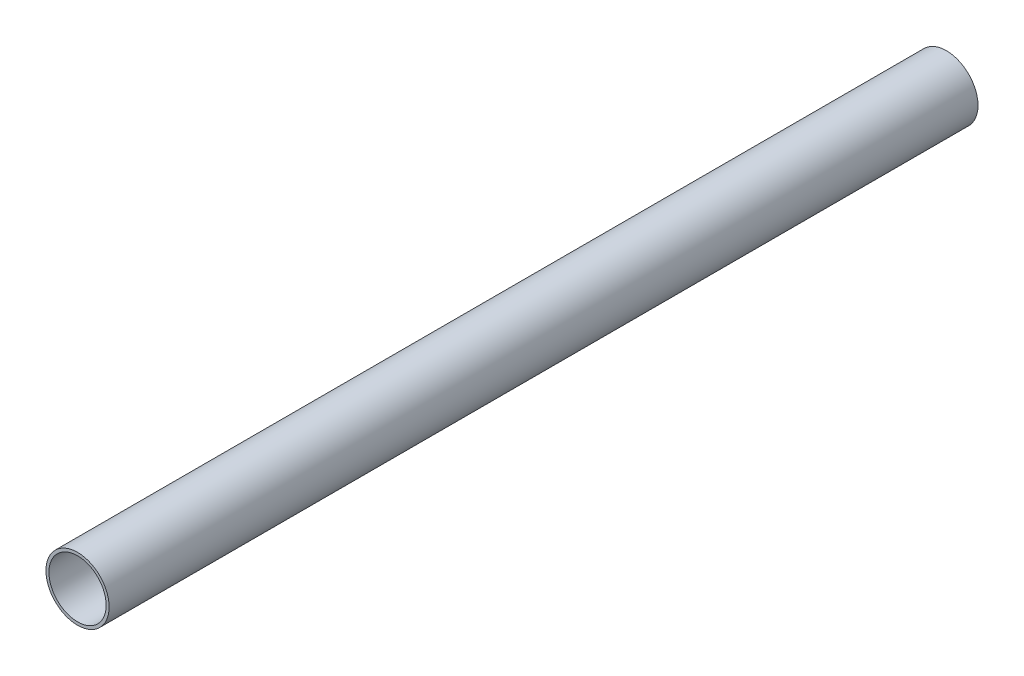
SolidWorks part; units mm, degrees
material "5052 Alloy"
ref_plane "Front Plane" through (0, 0, 0) normal (0, 0, 1) x (1, 0, 0)
ref_plane "Top Plane" through (0, 0, 0) normal (0, 1, 0) x (1, 0, 0)
ref_plane "Right Plane" through (0, 0, 0) normal (1, 0, 0) x (0, 0, -1)
sketch "Sketch1" plane through (0, 0, 0) normal (0, 0, 1) x (1, 0, 0)
  circle A0 centre (0, 0) radius 8
  dimension "D1" = 16
extrude "Extrude1" add sketch "Sketch1" against normal blind 220
sketch "Sketch2" plane through (0, 0, 0) normal (0, 0, 1) x (1, 0, 0)
  circle A0 centre (0, 0) radius 7.25
  dimension "D1" = 14.5
extrude "Cut-Extrude1" cut sketch "Sketch2" against normal through all
